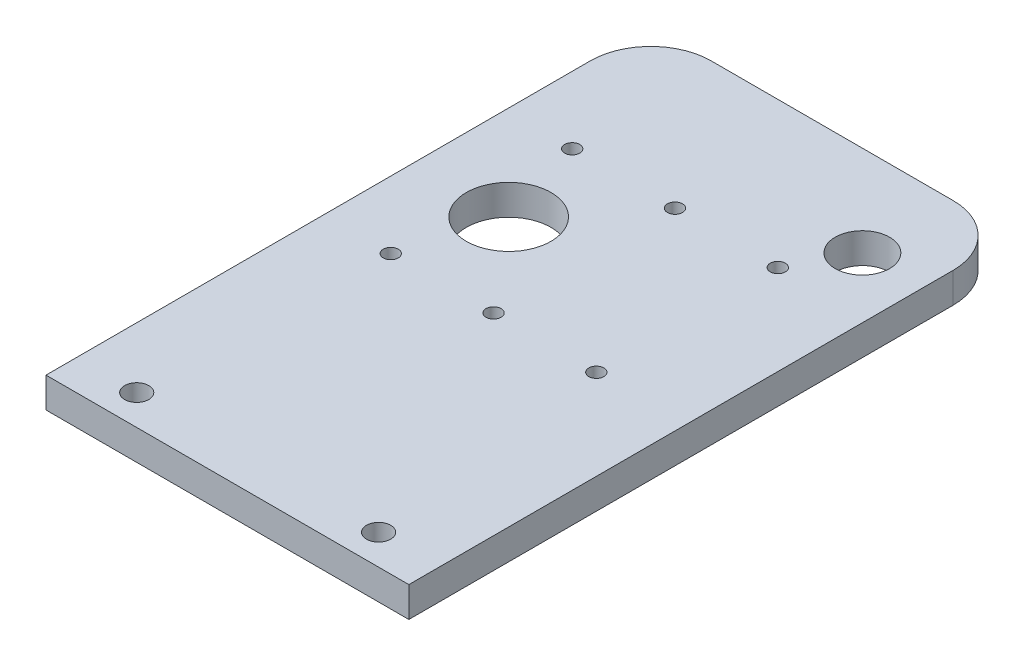
SolidWorks part; units mm, degrees
ref_plane "前视基准面" through (0, 0, 0) normal (0, 0, 1) x (1, 0, 0)
ref_plane "上视基准面" through (0, 0, 0) normal (0, 1, 0) x (1, 0, 0)
ref_plane "右视基准面" through (0, 0, 0) normal (1, 0, 0) x (0, 0, -1)
sketch "草图1" plane through (0, 0, 0) normal (0, 1, 0) x (1, 0, 0)
  line L0 (-65.3287, 31.4507) -> (-65.3287, -58.5493)
  line L1 (-55.3287, 41.4507) -> (-15.3287, 41.4507)
  line L4 (-5.3287, 31.4507) -> (-5.3287, 2.3607)
  line L13 (-65.3287, -58.5493) -> (-55.3287, -58.5493)
  line L14 (-55.3287, -58.5493) -> (-15.3287, -58.5493)
  line L15 (-15.3287, -58.5493) -> (-5.3287, -58.5493)
  line L16 (-5.3287, -58.5493) -> (-5.3287, 2.3607)
  circle A0 centre (-49.7287, 2.3607) radius 7
  circle A1 centre (-55.3287, -53.5493) radius 2
  circle A2 centre (-15.3287, -53.5493) radius 2
  circle A3 centre (-15.3287, 26.4507) radius 4.5
  circle A4 centre (-54.2287, 17.3607) radius 1.25
  circle A5 centre (-37.2287, 17.3607) radius 1.25
  circle A6 centre (-20.2287, 17.3607) radius 1.25
  circle A7 centre (-54.2287, -12.6393) radius 1.25
  circle A8 centre (-37.2287, -12.6393) radius 1.25
  circle A9 centre (-20.2287, -12.6393) radius 1.25
  arc A10 (-65.3287, 31.4507) -> (-55.3287, 41.4507) centre (-55.3287, 31.4507) cw
  arc A11 (-15.3287, 41.4507) -> (-5.3287, 31.4507) centre (-15.3287, 31.4507) cw
  point P3 (0, 0)
  point P5 (0, 0)
  point P32 (-65.3287, 41.4507)
  dimension "D18" = 10
  dimension "D2" = 10
  dimension "D1" = 100
  dimension "D6" = 44.4
  dimension "D9" = 17
  dimension "D10" = 17
  dimension "D12" = 17
  dimension "D13" = 17
  dimension "D14" = 10
  dimension "D15" = 40
  dimension "D16" = 10
  dimension "D17" = 5
extrude "凸台-拉伸1" add sketch "草图1" along normal blind 5
